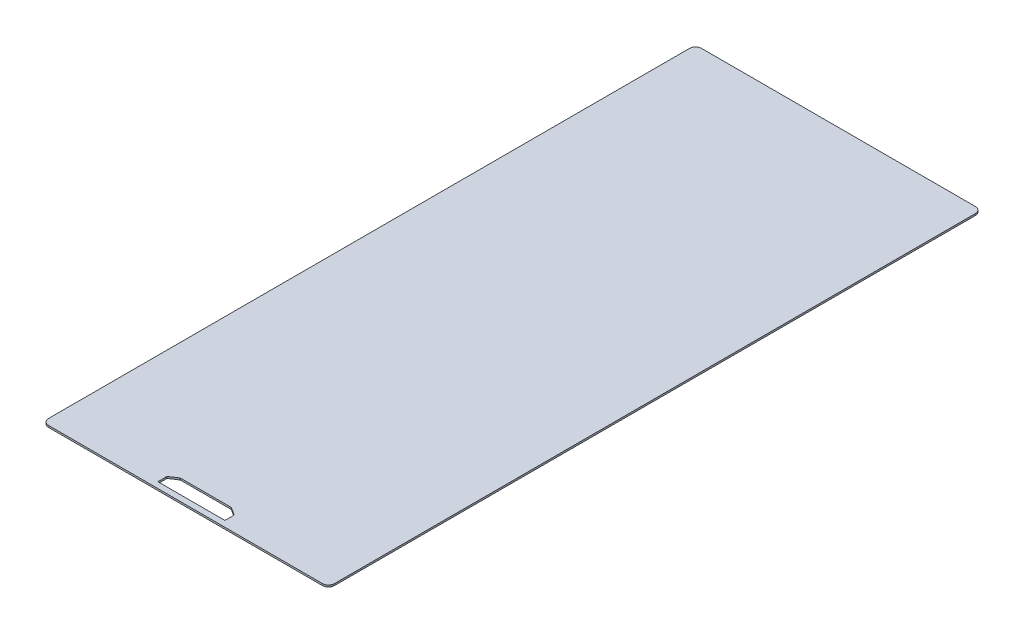
SolidWorks part; units mm, degrees
ref_plane "Front Plane" through (0, 0, 0) normal (0, 0, 1) x (1, 0, 0)
ref_plane "Top Plane" through (0, 0, 0) normal (0, 1, 0) x (1, 0, 0)
ref_plane "Right Plane" through (0, 0, 0) normal (1, 0, 0) x (0, 0, -1)
sketch "Sketch1" plane through (0, 0, 0) normal (0, 1, 0) x (1, 0, 0)
  line L1 (-231.5, -551.5) -> (231.5, -551.5)
  line L2 (-241.5, -541.5) -> (-241.5, 541.5)
  line L3 (-231.5, 551.5) -> (231.5, 551.5)
  line L4 (241.5, -541.5) -> (241.5, 541.5)
  line L5 (-241.5, -551.5) -> (241.5, 551.5) construction
  line L6 (-241.5, 551.5) -> (241.5, -551.5) construction
  arc A0 (231.5, -551.5) -> (241.5, -541.5) centre (231.5, -541.5) ccw
  arc A1 (-231.5, -551.5) -> (-241.5, -541.5) centre (-231.5, -541.5) cw
  arc A2 (-241.5, 541.5) -> (-231.5, 551.5) centre (-231.5, 541.5) cw
  arc A3 (231.5, 551.5) -> (241.5, 541.5) centre (231.5, 541.5) cw
  point P0 (0, 0)
  dimension "D3" = 10
  dimension "D1" = 483
  dimension "D2" = 1103
extrude "Boss-Extrude1" add sketch "Sketch1" along normal blind 3
sketch "Sketch2" plane through (0, 3, 0) normal (0, 1, 0) x (1, 0, 0)
  line L0 (0, -551.5) -> (0, -541.5) construction
  line L1 (-231.5, -551.5) -> (231.5, -551.5) construction
  line L2 (-56.625, -541.5) -> (56.625, -541.5)
  line L3 (56.625, -541.5) -> (56.625, -527.3399)
  line L4 (55.5092, -525.2581) -> (43.9303, -517.5592)
  line L5 (42.5461, -517.141) -> (-42.5461, -517.141)
  line L6 (-43.9303, -517.5592) -> (-55.5092, -525.2581)
  line L7 (-56.625, -527.3399) -> (-56.625, -541.5)
  arc A0 (56.625, -527.3399) -> (55.5092, -525.2581) centre (54.125, -527.3399) ccw
  arc A1 (43.9303, -517.5592) -> (42.5461, -517.141) centre (42.5461, -519.641) ccw
  arc A2 (-55.5092, -525.2581) -> (-56.625, -527.3399) centre (-54.125, -527.3399) ccw
  arc A3 (-42.5461, -517.141) -> (-43.9303, -517.5592) centre (-42.5461, -519.641) ccw
  point P5 (30.4882, -472.4982)
  point P8 (0, -541.5)
  point P15 (56.625, -526)
  point P18 (43.3014, -517.141)
  point P23 (-43.3014, -517.141)
  dimension "D6" = 2.5
  dimension "D1" = 113.25
  dimension "D2" = 15.5
  dimension "D3" = 16
  dimension "D4" = 86.6028
  dimension "D5" = 10
extrude "Cut-Extrude1" cut sketch "Sketch2" against normal through all
